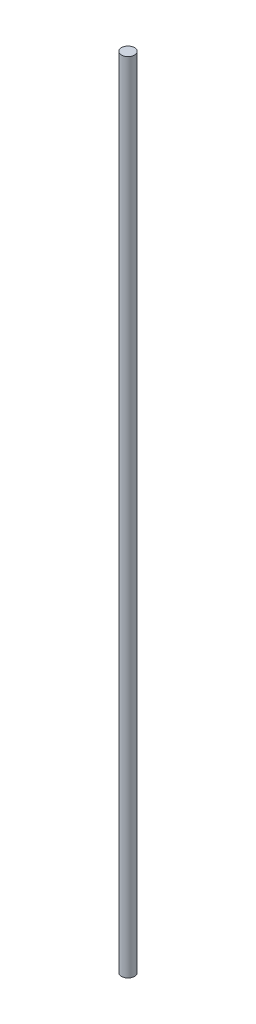
SolidWorks part; units mm, degrees
ref_plane "Alzado" through (0, 0, 0) normal (0, 0, 1) x (1, 0, 0)
ref_plane "Planta" through (0, 0, 0) normal (0, 1, 0) x (1, 0, 0)
ref_plane "Vista lateral" through (0, 0, 0) normal (1, 0, 0) x (0, 0, -1)
sketch "Croquis5" plane through (0, 0, 0) normal (0, 1, 0) x (1, 0, 0)
  circle A0 centre (0, 0) radius 3
  dimension "DIAMETER" = 6
extrude "Saliente-Extruir3" add sketch "Croquis5" along normal mid plane 368
